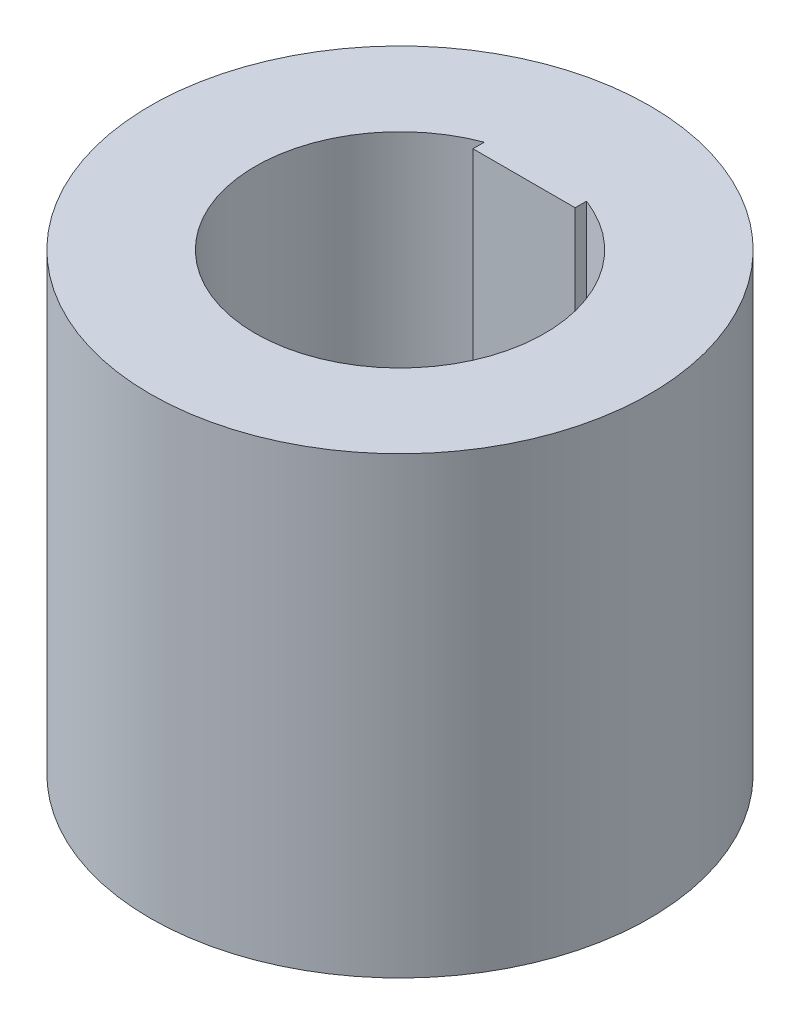
SolidWorks part; units mm, degrees
ref_plane "Plane1" through (0, 0, 0) normal (0, 0, 1) x (1, 0, 0)
ref_plane "Plane2" through (0, 0, 0) normal (0, 1, 0) x (1, 0, 0)
ref_plane "Plane3" through (0, 0, 0) normal (1, 0, 0) x (0, 0, -1)
other "Configuration Table"
sketch "Sketch1" plane through (0, 0, 0) normal (0, 1, 0) x (1, 0, 0)
  line L1 (-0.9, 2.3859) -> (0.9, 2.3859) construction
  line L2 (-0.9, 2.3859) -> (-0.9, 2.1859)
  line L3 (-0.9, 2.1859) -> (0.9, 2.1859)
  line L4 (0.9, 2.3859) -> (0.9, 2.1859)
  circle A0 centre (0, 0) radius 4.4
  circle A1 centre (0, 0) radius 2.55
  point P8 (1.0964, 2.3023)
  dimension "D1" = 8.8
  dimension "D2" = 5.1
  dimension "D3" = 1.8
  dimension "D4" = 0.2
extrude "Boss-Extrude1" add sketch "Sketch1" along normal mid plane 8 contours A1 L1 | L1 L2 L3 L4 | A0 A1
equation "\"pitch\"= 1 / \"Pitch@HoldingSke\""
equation "\"pd\"= \"Num_teeth@HoldingSke\" /  ( \"pitch\" * cos ( \"Helix_angle@HoldingSke\" )  ) "
equation "\"Pitch_dia@TooCutSkeRH\" = \"pd\""
equation "\"addendum\"= 1 / \"pitch\""
equation "\"dedendum\"= 1.25 / \"pitch\""
equation "\"whole_depth\"=\"addendum\" + \"dedendum\""
equation "\"Diameter@BasProSke\" = \"pd\" + (2 / \"pitch\")"
equation "\"Overcut_dia@TooCutSkeRH\" = 1.03 * \"Diameter@BasProSke\""
equation "\"transverse_pressure_angle\"= atn(tan(\"Ap@HoldingSke\") / cos(\"Helix_angle@HoldingSke\"))"
equation "\"transverse_pitch\"= \"Num_teeth@HoldingSke\" / \"pd\""
equation "\"Root_dia@TooCutSkeRH\" = \"pd\" -  ( 2 * \"dedendum\" ) "
equation "\"Base_dia@TooCutSkeRH\" = \"pd\" *  cos(\"transverse_pressure_angle\")"
equation "\"transverse_tooth_thickness\"=  ( \"pd\" * pi )  /  ( 2 * \"Num_teeth@HoldingSke\" ) "
equation "\"Factored_DP@HoldingSke\" = \"pitch\"  / cos(\"Helix_angle@HoldingSke\")"
equation "\"Half_ang@TooCutSkeRH\" = 180 / \"Num_teeth@HoldingSke\""
equation "\"Half_CT@TooCutSkeRH\" = \"transverse_tooth_thickness\" / 2"
equation "\"Flank_rad@TooCutSkeRH\" = \"Num_teeth@HoldingSke\" / \"pitch\" / 4"
equation "\"Root_fillet@TooCutSkeRH\" = \"Clearance_fac@HoldingSke\" / \"pitch\" + \"Dedendum_add@HoldingSke\""
equation "\"Thickness@HoldingSke\" = \"Width@HoldingSke\""
equation "\"MHD1\"= \"Num_teeth@HoldingSke\"  / \"pitch\" - 2 * \"Dedendum_fac@HoldingSke\"/ \"Factored_DP@HoldingSke\" - 2 * \"Dedendum_add@HoldingSke\""
equation "\"MBD1\"= \"Num_teeth@HoldingSke\"  / \"pitch\" - 2 * \"Dedendum_fac@HoldingSke\"/ \"Factored_DP@HoldingSke\" - 2 * \"Dedendum_add@HoldingSke\" - 0.002"
equation "\"MHD2\"= ((sgn( \"MHD1\" - \"Hub_dia@HoldingSke\" )-1)*( \"MHD1\" - \"Hub_dia@HoldingSke\" ))/-2+ \"Hub_dia@HoldingSke\""
equation "\"MBD@HoldingSke\" = ((sgn( \"MBD1\" - \"Bore@HoldingSke\" )-1)*( \"MBD1\" - \"Bore@HoldingSke\" ))/-2+ \"Bore@HoldingSke\""
equation "\"OAL@HoldingSke\" = ((sgn( \"Thickness@HoldingSke\" - \"Overall_len@HoldingSke\" )+1)*( \"Thickness@HoldingSke\" - \"Overall_len@HoldingSke\" ))/2 + \"Overall_len@HoldingSke\" + 0.000002"
equation "\"Num_teeth1\"= int( \"Show_teeth@HoldingSke\" ) + 1"
equation "\"Num_teeth2\"= ((sgn( \"Num_teeth1\" - \"Num_teeth@HoldingSke\" )-1)*( \"Num_teeth1\" - \"Num_teeth@HoldingSke\" ))/-2+ \"Num_teeth@HoldingSke\""
equation "\"Num_teeth@TeethCutsRH\" = ((sgn( \"Num_teeth2\" - 2.0)+1)*( \"Num_teeth2\" - 2.0))/2 +2.0"
equation "\"Angle@TeethCutsRH\" = 360.0 / \"Num_teeth@HoldingSke\""
equation "\"Num_teeth@TeethCutsLH\" = \"Num_teeth@TeethCutsRH\""
equation "\"Angle@TeethCutsLH\" = 360.0 / \"Num_teeth@HoldingSke\""
equation "'\"Diameter@BasProSke\" = \"Num_teeth@HoldingSke\" / \"Pitch@HoldingSke\" + 2 * \"Addendum_fac@HoldingSke\" / \"Factored_DP@HoldingSke\""
equation "\"Thickness@BasProSke\"  = \"Thickness@HoldingSke\""
equation "' \"Fillet_rad@BasProSke\" =  \"Thickness@HoldingSke\" * 0.05"
equation "' \"Fillet_rad@BasProSke\" = \"Thickness@HoldingSke\" * 0.05"
equation "\"MHD@HoldingSke\" = ((sgn( \"MHD2\" - \"Root_dia@TooCutSkeRH\" )-1)*( \"MHD2\" - \"Root_dia@TooCutSkeRH\" ))/-2+ \"Root_dia@TooCutSkeRH\""
equation "\"Diameter@HubNeaOneSke\" = \"MHD@HoldingSke\""
equation "\"Length@HubNearOne\" = \"OAL@HoldingSke\" - \"Thickness@BasProSke\""
equation "\"Diameter@HubNeaBotSke\" = \"MHD@HoldingSke\""
equation "\"Length@HubNearBoth\" = ( \"OAL@HoldingSke\" - \"Thickness@BasProSke\" ) / 2.0"
equation "\"Thickness@FarPln\" = \"Thickness@BasProSke\""
equation "\"Diameter@HubFarSke\" = \"MHD@HoldingSke\""
equation "\"Length@HubFar\" = ( \"OAL@HoldingSke\" - \"Thickness@BasProSke\" ) / 2.0"
equation "\"Diameter@BorSke\" = \"MBD@HoldingSke\""
equation "\"D1@Bore\" = \"OAL@HoldingSke\" * 2.5"
equation "\"D1@Keyway\" = \"OAL@HoldingSke\" * 2.5"
equation "\"Offset@KeySke\" = \"T_dim@HoldingSke\" + (\"MBD@HoldingSke\"/ 2.0)"
equation "\"Pitch@HelixRH\" = (pi * \"Diameter@BasProSke\") * (1/tan(\"Helix_angle@HoldingSke\"))"
equation "\"Pitch@HelixLH\" = (pi * \"Diameter@BasProSke\") * (1/tan(\"Helix_angle@HoldingSke\"))"
equation "\"HelixLength@HelixRH\" = \"Thickness@BasProSke\""
equation "\"HelixLength@HelixLH\" = \"Thickness@BasProSke\""
